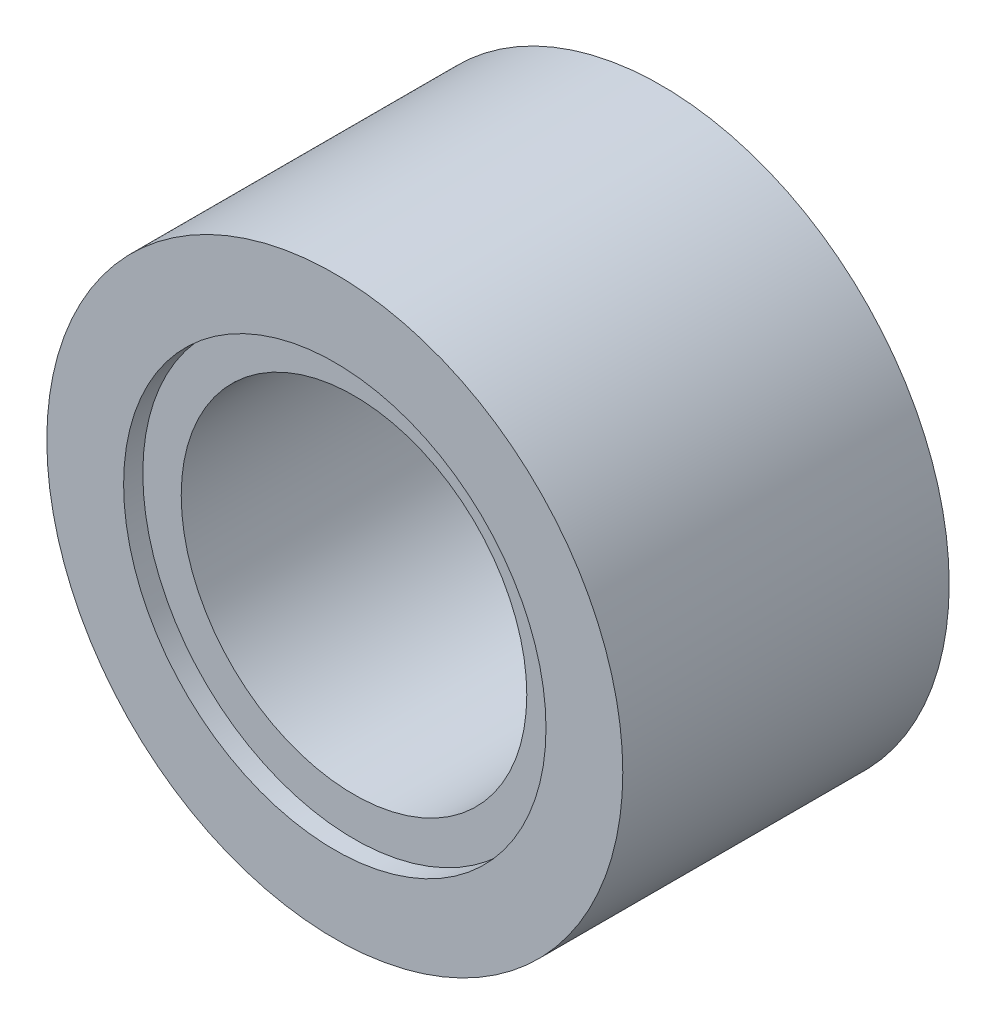
SolidWorks part; units mm, degrees
ref_plane "Front Plane" through (0, 0, 0) normal (0, 0, 1) x (1, 0, 0)
ref_plane "Top Plane" through (0, 0, 0) normal (0, 1, 0) x (1, 0, 0)
ref_plane "Right Plane" through (0, 0, 0) normal (1, 0, 0) x (0, 0, -1)
sketch "Sketch1" plane through (0, 0, 0) normal (0, 0, 1) x (1, 0, 0)
  circle A0 centre (0, 0) radius 30
  dimension "D1" = 60
extrude "Boss-Extrude1" add sketch "Sketch1" along normal blind 34
sketch "Sketch2" plane through (0, 0, 34) normal (0, 0, 1) x (1, 0, 0)
  circle A0 centre (0, 0) radius 18
  dimension "D1" = 36
extrude "Cut-Extrude1" cut sketch "Sketch2" against normal blind 30
sketch "Sketch4" plane through (0, 0, 34) normal (0, 0, 1) x (1, 0, 0)
  circle A0 centre (0, 0) radius 22
  dimension "D1" = 44
extrude "Cut-Extrude2" cut sketch "Sketch4" against normal blind 2
